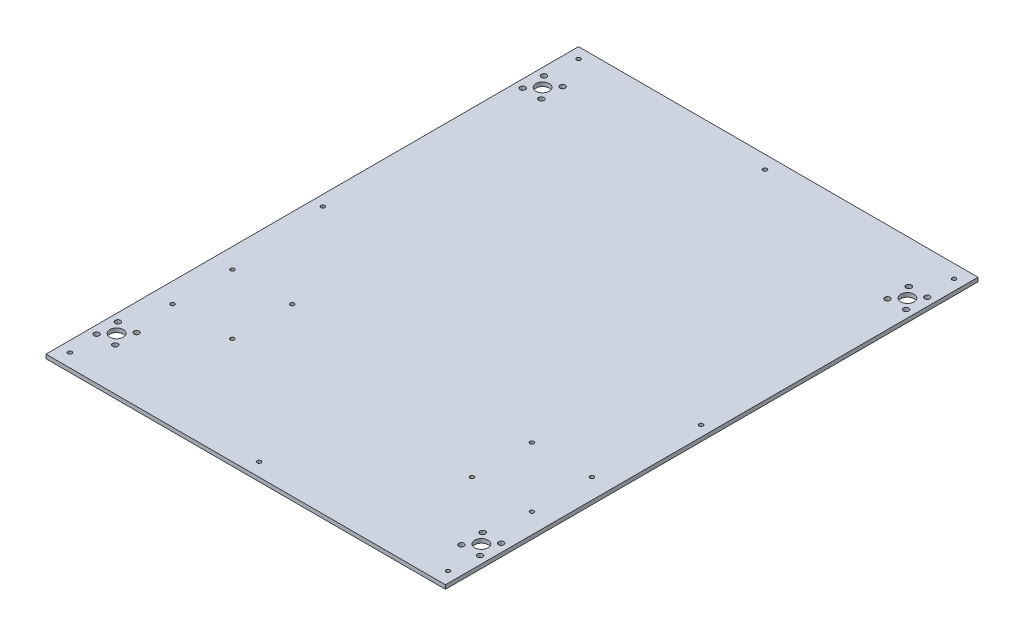
SolidWorks part; units mm, degrees
material "A-玻璃纤维"
ref_plane "前视基准面" through (0, 0, 0) normal (0, 0, 1) x (1, 0, 0)
ref_plane "上视基准面" through (0, 0, 0) normal (0, 1, 0) x (1, 0, 0)
ref_plane "右视基准面" through (0, 0, 0) normal (1, 0, 0) x (0, 0, -1)
sketch "草图1" plane through (0, 0, 0) normal (0, 1, 0) x (1, 0, 0)
  line L0 (0, 295.9627) -> (0, -253.3648) construction
  line L1 (-150, 200) -> (150, 200)
  line L2 (-150, 200) -> (-150, -200)
  line L3 (-150, -200) -> (150, -200)
  line L4 (150, 200) -> (150, -200)
  line L5 (-150, 200) -> (150, -200) construction
  line L6 (-150, -200) -> (150, 200) construction
  line L7 (-137, 310.1491) -> (-137, -253.3648) construction
  line L8 (137, 342.4725) -> (137, -253.3969) construction
  line L9 (-227.306, 0) -> (206.2046, 0) construction
  line L10 (-211.6958, 160) -> (161.4725, 160) construction
  circle A0 centre (-137, 160) radius 5
  circle A1 centre (137, 160) radius 5
  circle A2 centre (137, -160) radius 5
  circle A3 centre (-137, -160) radius 5
  circle A4 centre (-144, 168) radius 2
  circle A5 centre (-130, 168) radius 2
  circle A6 centre (-130, 152) radius 2
  circle A7 centre (-144, 152) radius 2
  circle A8 centre (130, 152) radius 2
  circle A9 centre (144, 152) radius 2
  circle A10 centre (130, 168) radius 2
  circle A11 centre (144, 168) radius 2
  circle A12 centre (144, -152) radius 2
  circle A13 centre (130, -152) radius 2
  circle A14 centre (144, -168) radius 2
  circle A15 centre (130, -168) radius 2
  circle A16 centre (-144, -152) radius 2
  circle A17 centre (-130, -152) radius 2
  circle A18 centre (-130, -168) radius 2
  circle A19 centre (-144, -168) radius 2
  point P0 (0, 0)
  dimension "D5" = 10
  dimension "D6" = 10
  dimension "D7" = 10
  dimension "D8" = 10
  dimension "D13" = 4
  dimension "D14" = 4
  dimension "D15" = 4
  dimension "D16" = 4
  dimension "D1" = 300
  dimension "D2" = 400
  dimension "D3" = 13
  dimension "D4" = 13
  dimension "D9" = 160
  dimension "D10" = 160
  dimension "D11" = 274
  dimension "D12" = 274
  dimension "D17" = 8
  dimension "D18" = 16
  dimension "D19" = 14
  dimension "D20" = 14
  dimension "D21" = 7
  dimension "D22" = 14
  dimension "D23" = 8
  dimension "D24" = 16
extrude "凸台-拉伸1" add sketch "草图1" along normal blind 3
sketch "草图2" plane through (0, 3, 0) normal (0, 1, 0) x (1, 0, 0)
  line L1 (0, 223.3455) -> (0, -251.8689) construction
  line L4 (-180.4529, 0) -> (164.3101, 0) construction
sketch "草图3" plane through (0, 3, 0) normal (0, 1, 0) x (1, 0, 0)
  line L0 (-201.5106, 0) -> (324.7484, 0) construction
  line L1 (-201.5106, 185) -> (260.3539, 185) construction
  line L2 (0, 219.5521) -> (0, -230.0995) construction
  line L3 (-201.5106, 162) -> (276.4525, 162) construction
  line L4 (150, 200) -> (-150, 200) construction
  line L5 (-90, 200) -> (-90, 138.098) construction
  circle A0 centre (-100, 185) radius 1.5
  circle A1 centre (-80, 185) radius 1.5
  circle A2 centre (90, 162) radius 1.5
  circle A3 centre (80, 185) radius 1.5
  circle A4 centre (-90, 162) radius 1.5
  circle A5 centre (100, 185) radius 1.5
  circle A6 centre (90, -162) radius 1.5
  circle A7 centre (100, -185) radius 1.5
  circle A8 centre (80, -185) radius 1.5
  circle A9 centre (-90, -162) radius 1.5
  circle A10 centre (-80, -185) radius 1.5
  circle A11 centre (-100, -185) radius 1.5
  dimension "D4" = 3
  dimension "D5" = 3
  dimension "D6" = 3
  dimension "D1" = 15
  dimension "D2" = 23
  dimension "D3" = 20
  dimension "D7" = 10
  dimension "D8" = 0
  dimension "D9" = 90
sketch "草图4" plane through (0, 3, 0) normal (0, 1, 0) x (1, 0, 0)
  line L0 (-180.4529, 0) -> (164.3101, 0) construction
  line L1 (0, 223.3455) -> (0, -251.8689) construction
  line L2 (-150, -200) -> (150, -200) construction
  line L3 (-150, 200) -> (-150, -200) construction
  line L5 (150, -200) -> (150, 200) construction
  line L8 (150, 200) -> (-150, 200) construction
  circle A0 centre (-142, -190) radius 1.5
  circle A1 centre (142, -190) radius 1.5
  circle A2 centre (142, 0) radius 1.5
  circle A3 centre (-142, 0) radius 1.5
  circle A4 centre (-142, 192) radius 1.5
  circle A5 centre (142, 190) radius 1.5
  circle A6 centre (0, 190) radius 1.5
  circle A7 centre (0, -190) radius 1.5
  dimension "D6" = 3
  dimension "D7" = 3
  dimension "D8" = 3
  dimension "D10" = 3
  dimension "D11" = 3
  dimension "D13" = 8
  dimension "D15" = 3
  dimension "D17" = 3
  dimension "D18" = 3
  dimension "D1" = 10
  dimension "D2" = 8
  dimension "D3" = 10
  dimension "D4" = 10
  dimension "D5" = 8
  dimension "D9" = 8
  dimension "D12" = 8
  dimension "D14" = 10
  dimension "D16" = 10
  dimension "D19" = 8
  dimension "D20" = 8
extrude "切除-拉伸1" cut sketch "草图4" against normal through all
sketch "草图5" plane through (0, 0, 0) normal (0, -1, 0) x (1, 0, 0)
  line L3 (0, 228.1448) -> (0, -220.8851) construction
  circle A0 centre (-135, 120) radius 1.5
  circle A1 centre (-90, 120) radius 1.5
  circle A2 centre (-135, 75) radius 1.5
  circle A3 centre (-90, 75) radius 1.5
  circle A4 centre (90, 75) radius 1.5
  circle A5 centre (135, 75) radius 1.5
  circle A6 centre (90, 120) radius 1.5
  circle A7 centre (135, 120) radius 1.5
extrude "切除-拉伸2" cut sketch "草图5" against normal blind 10
ref_plane "基准面1" through (-201.5106, 3, 0) normal (1, 0, 0) x (0, 0, -1)
